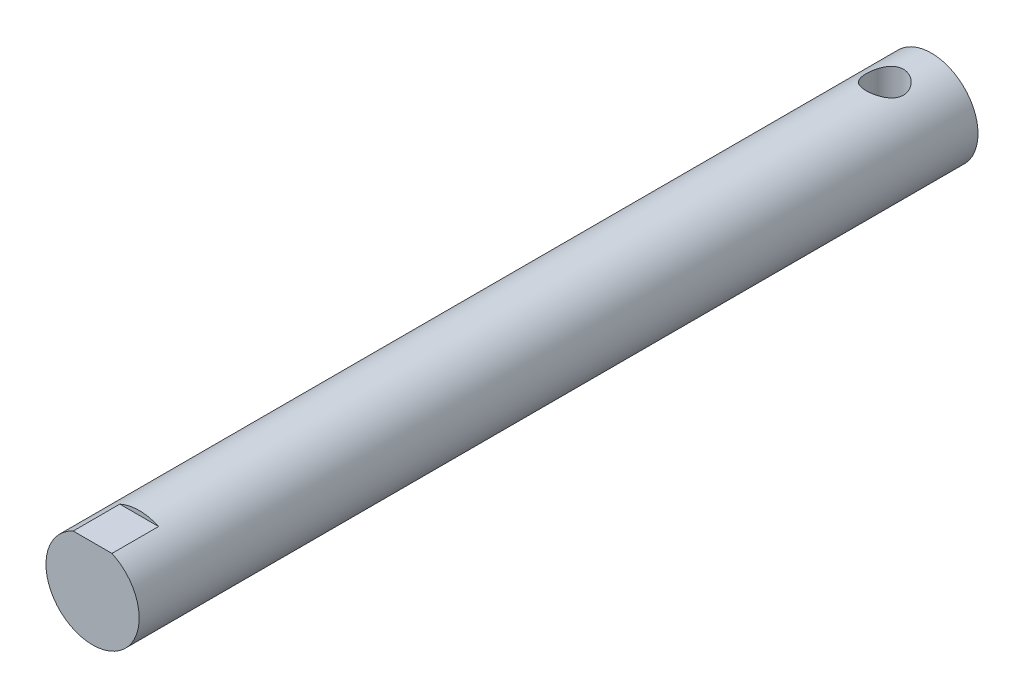
SolidWorks part; units mm, degrees
ref_plane "Front Plane" through (0, 0, 0) normal (0, 0, 1) x (1, 0, 0)
ref_plane "Top Plane" through (0, 0, 0) normal (0, 1, 0) x (1, 0, 0)
ref_plane "Right Plane" through (0, 0, 0) normal (1, 0, 0) x (0, 0, -1)
sketch "Sketch1" plane through (0, 0, 0) normal (0, 0, 1) x (1, 0, 0)
  circle A0 centre (0, 0) radius 10
  dimension "D1" = 20
extrude "Boss-Extrude1" add sketch "Sketch1" along normal blind 180
sketch "Sketch2" plane through (0, 0, 0) normal (0, 1, 0) x (1, 0, 0)
  line L0 (10, -10) -> (0, -10) construction
  line L1 (10, -180) -> (10, 0) construction
  line L2 (0, -10) -> (0, 0) construction
  circle A0 centre (0, -10) radius 4
  dimension "D1" = 8
extrude "Cut-Extrude1" cut sketch "Sketch2" against normal through all both and the other way through all
sketch "Sketch3" plane through (0, 0, 180) normal (0, 0, 1) x (1, 0, 0)
  line L0 (-4.1615, 9.0929) -> (4.1615, 9.0929)
  circle A0 centre (0, 0) radius 10 construction
  circle A2 centre (0, 0) radius 10
  arc A3 (4.1615, 9.0929) -> (-4.1615, 9.0929) centre (0, 0) ccw
  dimension "D1" = 0
extrude "Cut-Extrude2" cut sketch "Sketch3" against normal blind 10
